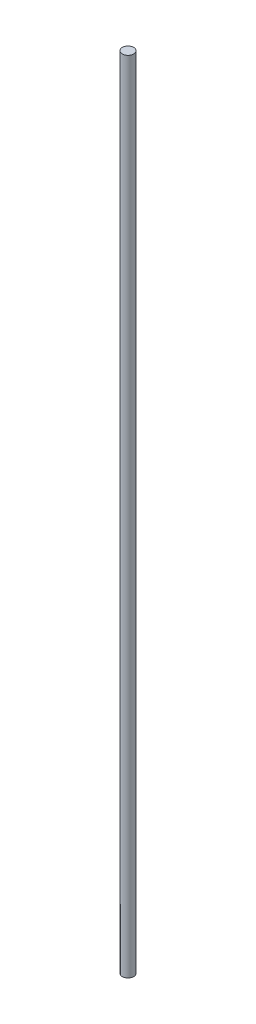
SolidWorks part; units mm, degrees
ref_plane "Front Plane" through (0, 0, 0) normal (0, 0, 1) x (1, 0, 0)
ref_plane "Top Plane" through (0, 0, 0) normal (0, 1, 0) x (1, 0, 0)
ref_plane "Right Plane" through (0, 0, 0) normal (1, 0, 0) x (0, 0, -1)
sketch "Sketch1" plane through (0, 0, 0) normal (0, 1, 0) x (1, 0, 0)
  circle A0 centre (0, 0) radius 4
  dimension "D1" = 8
extrude "Boss-Extrude1" add sketch "Sketch1" along normal blind 560
